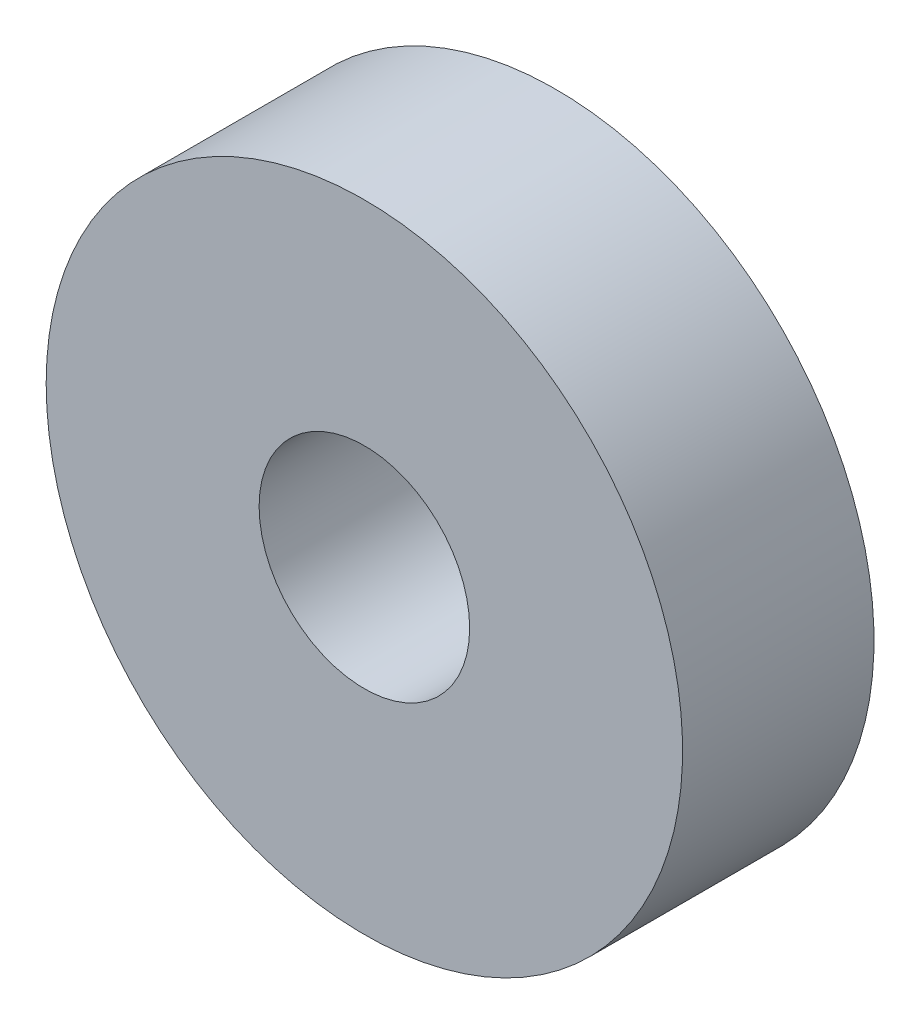
SolidWorks part; units mm, degrees
ref_plane "前视基准面" through (0, 0, 0) normal (0, 0, 1) x (1, 0, 0)
ref_plane "上视基准面" through (0, 0, 0) normal (0, 1, 0) x (1, 0, 0)
ref_plane "右视基准面" through (0, 0, 0) normal (1, 0, 0) x (0, 0, -1)
ref_plane "基准面4" through (0, 0, 0) normal (0, -1, 0) x (1, 0, 0)
sketch "草图1" plane through (0, 0, 0) normal (0, -1, 0) x (1, 0, 0)
  line L0 (4.9872, 3) -> (1.35, 3)
  line L1 (1.35, 3) -> (1.35, 0)
  line L2 (1.35, 0) -> (4.9872, 0)
  line L3 (4.9872, 0) -> (4.9872, 3)
  line L4 (0, 3) -> (0, 0) construction
revolve "旋转1" add sketch "草图1" angle 360 about L4
sketch "草图2" plane through (0, 0, 3) normal (0, 0, 1) x (1, 0, 0)
  circle A0 centre (0, 0) radius 1.65
  dimension "D1" = 3.3
extrude "切除-拉伸1" cut sketch "草图2" against normal through all
